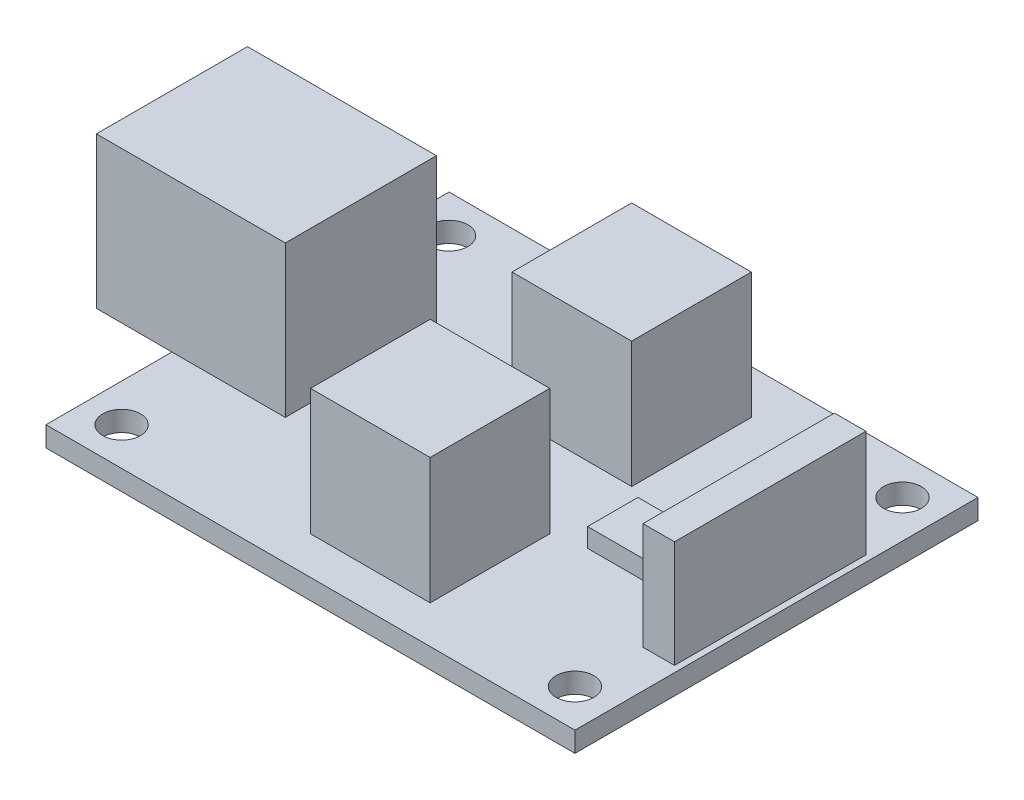
SolidWorks part; units mm, degrees
ref_plane "Front Plane" through (0, 0, 0) normal (0, 0, 1) x (1, 0, 0)
ref_plane "Top Plane" through (0, 0, 0) normal (0, 1, 0) x (1, 0, 0)
ref_plane "Right Plane" through (0, 0, 0) normal (1, 0, 0) x (0, 0, -1)
other "Configuration Table"
sketch "Sketch1" plane through (0, 0, 0) normal (0, 1, 0) x (1, 0, 0)
  line L1 (0, 0) -> (42, 0)
  line L2 (0, 0) -> (0, 32)
  line L3 (0, 32) -> (42, 32)
  line L4 (42, 0) -> (42, 32)
extrude "PCB" add sketch "Sketch1" along normal blind 1.6
sketch "Sketch2" plane through (0, 0, 0) normal (0, 1, 0) x (1, 0, 0)
  circle A0 centre (3, 3) radius 1.5
extrude "Mount_hole_1" cut sketch "Sketch2" against normal through all and the other way through all
sketch "Sketch3" plane through (0, 0, 0) normal (0, 1, 0) x (1, 0, 0)
  circle A0 centre (39, 3) radius 1.5
extrude "Mount_hole_2" cut sketch "Sketch3" against normal through all and the other way through all
sketch "Sketch4" plane through (0, 0, 0) normal (0, 1, 0) x (1, 0, 0)
  circle A0 centre (3, 29) radius 1.5
extrude "Mount_hole_3" cut sketch "Sketch4" against normal through all and the other way through all
sketch "Sketch5" plane through (0, 0, 0) normal (0, 1, 0) x (1, 0, 0)
  circle A0 centre (39, 29) radius 1.5
extrude "Mount_hole_4" cut sketch "Sketch5" against normal through all and the other way through all
sketch "Sketch6" plane through (0, 0, 0) normal (0, 1, 0) x (1, 0, 0)
  line L1 (-6, 10) -> (9, 10)
  line L2 (-6, 10) -> (-6, 22)
  line L3 (-6, 22) -> (9, 22)
  line L4 (9, 10) -> (9, 22)
extrude "BNC_socket" add sketch "Sketch6" along normal blind 12 from offset 1.6
sketch "Sketch7" plane through (0, 0, 0) normal (0, 1, 0) x (1, 0, 0)
  line L1 (18, 3) -> (27.5, 3)
  line L2 (18, 3) -> (18, 12.5)
  line L3 (18, 12.5) -> (27.5, 12.5)
  line L4 (27.5, 3) -> (27.5, 12.5)
extrude "Offset_pot" add sketch "Sketch7" along normal blind 10 from offset 1.6
sketch "Sketch8" plane through (0, 0, 0) normal (0, 1, 0) x (1, 0, 0)
  line L1 (18, 19) -> (27.5, 19)
  line L2 (18, 19) -> (18, 28.5)
  line L3 (18, 28.5) -> (27.5, 28.5)
  line L4 (27.5, 19) -> (27.5, 28.5)
extrude "Limit_pot" add sketch "Sketch8" along normal blind 10 from offset 1.6
sketch "Sketch9" plane through (0, 0, 0) normal (0, 1, 0) x (1, 0, 0)
  line L1 (30, 13) -> (35, 13)
  line L2 (30, 13) -> (30, 17)
  line L3 (30, 17) -> (35, 17)
  line L4 (35, 13) -> (35, 17)
extrude "Op_amp" add sketch "Sketch9" along normal blind 1.5 from offset 1.6
sketch "Sketch10" plane through (0, 0, 0) normal (0, 1, 0) x (1, 0, 0)
  line L1 (39, 8.4) -> (41.5, 8.4)
  line L2 (39, 8.4) -> (39, 23.6)
  line L3 (39, 23.6) -> (41.5, 23.6)
  line L4 (41.5, 8.4) -> (41.5, 23.6)
extrude "Header_6pin" add sketch "Sketch10" along normal blind 8.5 from offset 1.6
